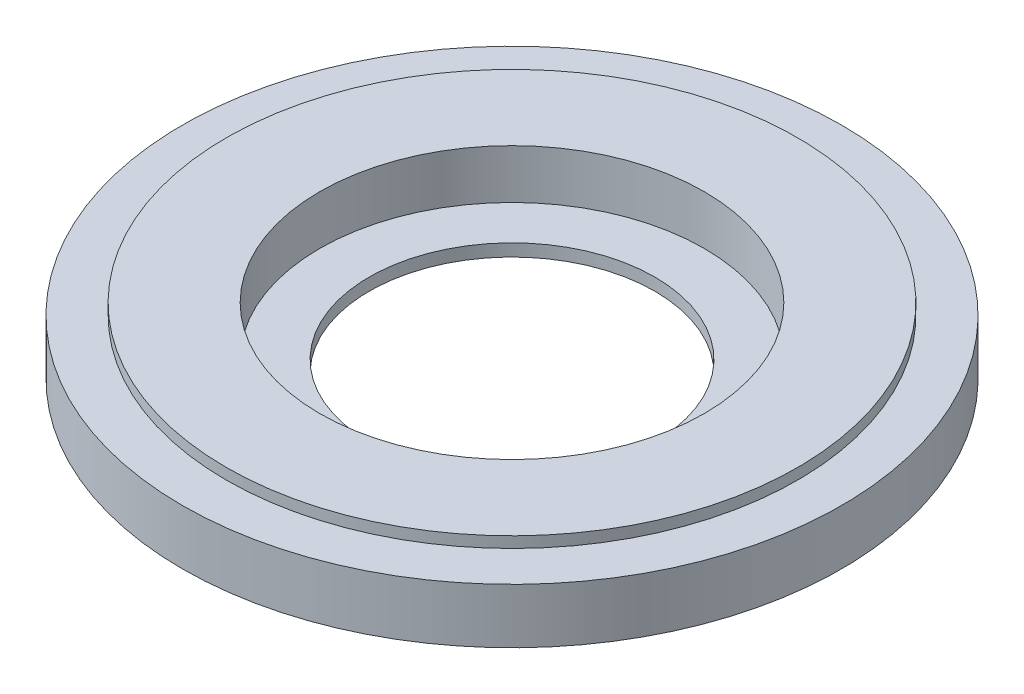
SolidWorks part; units mm, degrees
material "1.4511 (X3CrNb17)"
ref_plane "前视基准面" through (0, 0, 0) normal (0, 0, 1) x (1, 0, 0)
ref_plane "上视基准面" through (0, 0, 0) normal (0, 1, 0) x (1, 0, 0)
ref_plane "右视基准面" through (0, 0, 0) normal (1, 0, 0) x (0, 0, -1)
sketch "草图1" plane through (0, 0, 0) normal (0, 1, 0) x (1, 0, 0)
  circle A0 centre (0, 0) radius 30
  dimension "D1" = 60
extrude "凸台-拉伸1" add sketch "草图1" along normal blind 5
sketch "草图2" plane through (0, 5, 0) normal (0, 1, 0) x (1, 0, 0)
  circle A0 centre (0, 0) radius 26
  dimension "D1" = 52
extrude "凸台-拉伸2" add sketch "草图2" along normal blind 1
sketch "草图3" plane through (0, 0, 0) normal (0, -1, 0) x (1, 0, 0)
  circle A0 centre (0, 0) radius 18
  dimension "D1" = 36
extrude "切除-拉伸1" cut sketch "草图3" against normal blind 0.4
sketch "草图4" plane through (0, 6, 0) normal (0, 1, 0) x (1, 0, 0)
  circle A0 centre (0, 0) radius 17.5
  dimension "D1" = 35
extrude "切除-拉伸2" cut sketch "草图4" against normal blind 4.48
sketch "草图5" plane through (0, 1.52, 0) normal (0, 1, 0) x (1, 0, 0)
  circle A0 centre (0, 0) radius 13
  dimension "D1" = 26
extrude "切除-拉伸3" cut sketch "草图5" against normal through all
